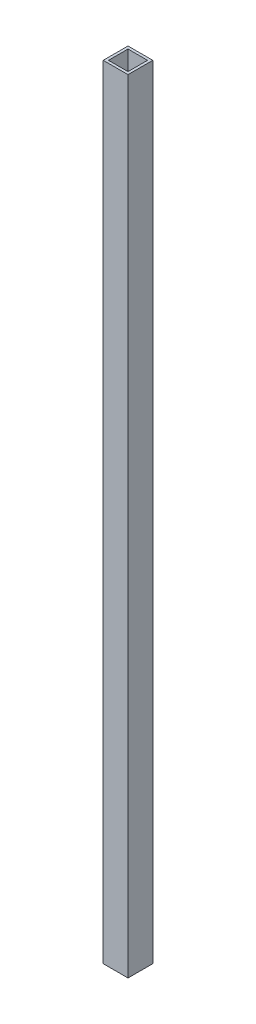
SolidWorks part; units mm, degrees
ref_plane "Front Plane" through (0, 0, 0) normal (0, 0, 1) x (1, 0, 0)
ref_plane "Top Plane" through (0, 0, 0) normal (0, 1, 0) x (1, 0, 0)
ref_plane "Right Plane" through (0, 0, 0) normal (1, 0, 0) x (0, 0, -1)
sketch "Sketch1" plane through (0, 0, 0) normal (0, 1, 0) x (1, 0, 0)
  line L1 (-9.5, -9.5) -> (9.5, -9.5)
  line L2 (-9.5, -9.5) -> (-9.5, 9.5)
  line L3 (-9.5, 9.5) -> (9.5, 9.5)
  line L4 (9.5, -9.5) -> (9.5, 9.5)
  line L5 (-9.5, -9.5) -> (9.5, 9.5) construction
  line L6 (-9.5, 9.5) -> (9.5, -9.5) construction
  point P0 (0, 0)
  dimension "D1" = 19
  dimension "D2" = 19
extrude "Extrude-Thin1" add sketch "Sketch1" along normal blind 600 thin thin type one direction reverse wall 2
